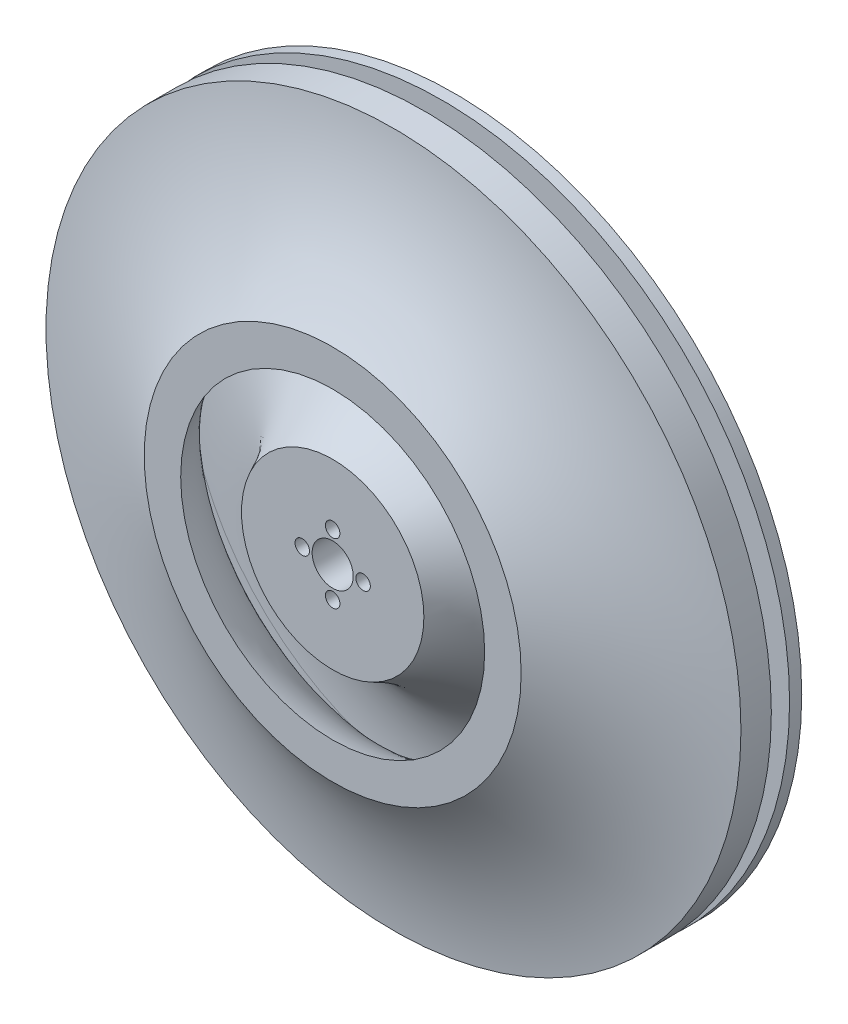
SolidWorks part; units mm, degrees
material "Titanium"
ref_plane "Front Plane" through (0, 0, 0) normal (1, 0, 0) x (0, 1, 0)
ref_plane "Top Plane" through (0, 0, 0) normal (0, 0, 1) x (0, 1, 0)
ref_plane "Right Plane" through (0, 0, 0) normal (0, 1, 0) x (-1, 0, 0)
sketch "Sketch1" plane through (0, 0, 0) normal (1, 0, 0) x (0, 1, 0)
  line L0 (-15, 20) -> (0, 20)
  line L1 (0, 20) -> (0, -15)
  line L2 (0, -15) -> (-12.5, -15)
  line L3 (-12.5, -15) -> (-12.5, 0)
  line L5 (-22.775, 0) -> (-22.775, 1)
  line L6 (-22.775, 1) -> (-25.025, 1)
  line L7 (-25.025, 1) -> (-25.025, 0)
  line L8 (-25.025, 0) -> (-26.775, 0)
  line L9 (-26.775, 0) -> (-26.775, 1)
  line L10 (-26.775, 1) -> (-29.025, 1)
  line L11 (-29.025, 1) -> (-29.025, 0)
  line L12 (-29.025, 0) -> (-30.775, 0)
  line L13 (-30.775, 0) -> (-30.775, 1)
  line L14 (-30.775, 1) -> (-33.025, 1)
  line L15 (-33.025, 1) -> (-33.025, 0)
  line L16 (-33.025, 0) -> (-34.775, 0)
  line L17 (-34.775, 0) -> (-34.775, 1)
  line L18 (-34.775, 1) -> (-37.025, 1)
  line L19 (-37.025, 1) -> (-37.025, 0)
  line L20 (-37.025, 0) -> (-57.15, 0)
  line L21 (-57.15, 0) -> (-57.15, 2)
  line L22 (-57.15, 2) -> (-42.15, 2)
  line L23 (-57.15, 5) -> (-42.15, 6.3123)
  line L26 (-57.15, 10) -> (-57.15, 5)
  line L27 (0, -15) -> (0, 0) construction
  line L28 (-22.775, 0) -> (-12.5, 0)
  line L29 (-31, 20) -> (-25, 20)
  arc A1 (-42.15, 2) -> (-15, 20) centre (-42.15, 31.4756) ccw
  arc A2 (-42.15, 6.3123) -> (-25, 20) centre (-43.8782, 26.0656) ccw
  arc A3 (-57.15, 10) -> (-31, 20) centre (-63.0731, 64.6801) ccw
  point P31 (-23.9, 1)
  point P32 (-27.9, 1)
  dimension "D1" = 57.15
  dimension "D13" = 20
  dimension "D15" = 31
  dimension "D16" = 55
  dimension "D2" = 12.5
  dimension "D3" = 11.4
  dimension "D4" = 4
  dimension "D5" = 1
  dimension "D6" = 15
  dimension "D7" = 3
  dimension "D8" = 2
  dimension "D9" = 15
  dimension "D10" = 10
  dimension "D11" = 15
  dimension "D12" = 5
  dimension "D14" = 10
  dimension "D17" = 1.75
ref_axis "Axis1" through (0, 0, 21) along (0, 0, -1)
revolve "Revolve1" add sketch "Sketch1" angle 360 about axis through (0, 0, 21) along (0, 0, -1)
sketch "Sketch2" plane through (0, 0, 0) normal (0, 0, 1) x (0, 1, 0)
  line L0 (-5, 0) -> (5, 0) construction
  line L1 (0, 5) -> (0, -5) construction
  circle A0 centre (0, 0) radius 3.3782
  circle A1 centre (0, 5) radius 1.1906
  circle A2 centre (5, 0) radius 1.1906
  circle A3 centre (0, -5) radius 1.1906
  circle A4 centre (-5, 0) radius 1.1906
  dimension "D1" = 2.3812
  dimension "D2" = 6.7564
  dimension "D3" = 10
extrude "Cut-Extrude1" cut sketch "Sketch2" along normal through all both and the other way through all contours A4 | A1 | A2 | A3 | A0
